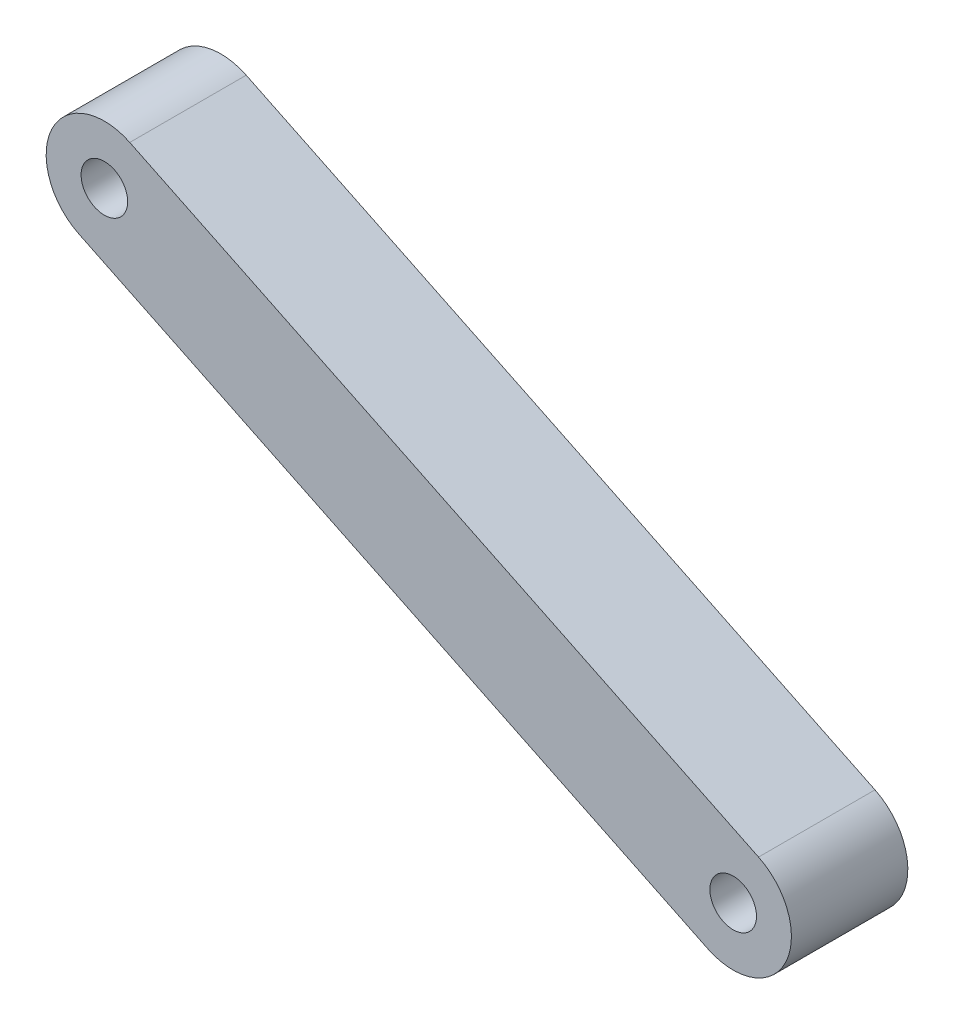
SolidWorks part; units mm, degrees
ref_plane "Front Plane" through (0, 0, 0) normal (0, 0, 1) x (1, 0, 0)
ref_plane "Top Plane" through (0, 0, 0) normal (0, 1, 0) x (1, 0, 0)
ref_plane "Right Plane" through (0, 0, 0) normal (1, 0, 0) x (0, 0, -1)
sketch "Sketch1" plane through (0, 0, 0) normal (0, 0, 1) x (1, 0, 0)
  line L45 (-61.3135, 11.2527) -> (-7.312, -14.8976)
  line L46 (-56.9551, 20.253) -> (-2.9537, -5.8973)
  circle A2 centre (-59.1343, 15.7529) radius 2
  circle A5 centre (-5.1329, -10.3975) radius 2
  arc A9 (-56.9551, 20.253) -> (-61.3135, 11.2527) centre (-59.1343, 15.7529) ccw
  arc A10 (-7.312, -14.8976) -> (-2.9537, -5.8973) centre (-5.1329, -10.3975) ccw
  dimension "D6" = 60
extrude "Boss-Extrude1" add sketch "Sketch1" along normal blind 10
